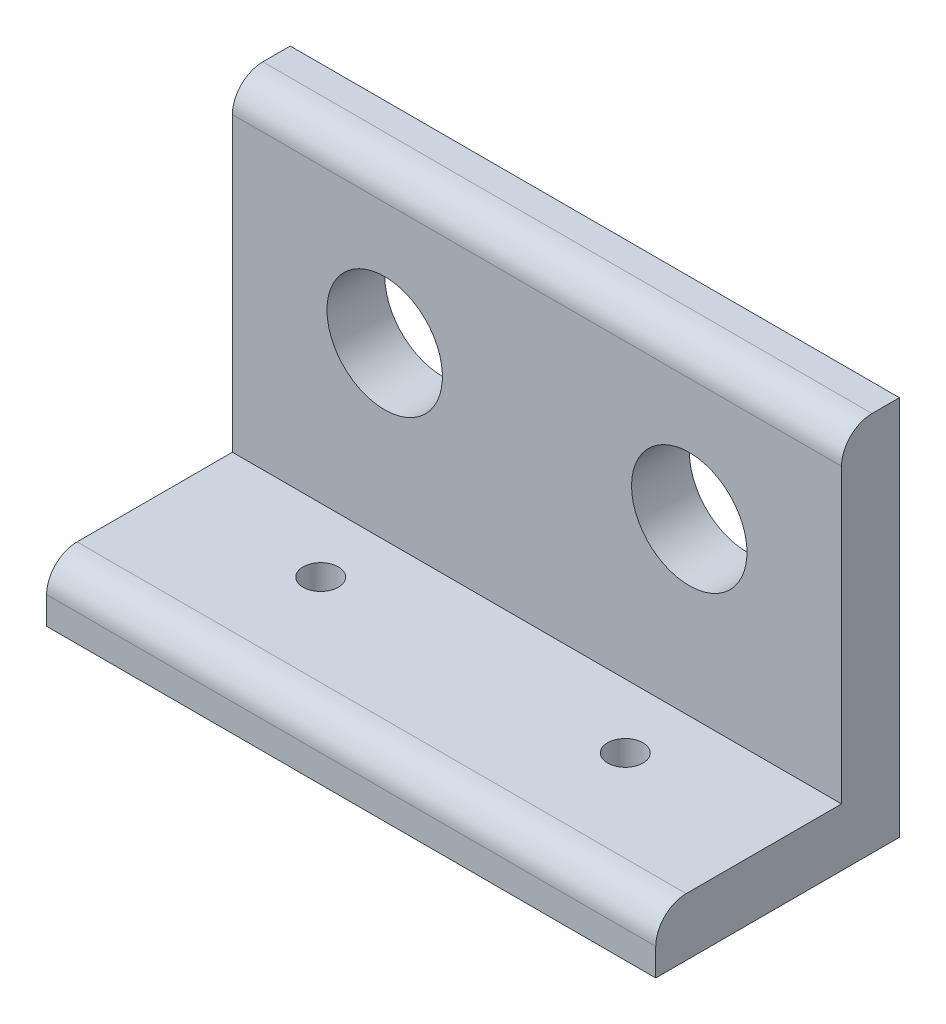
SolidWorks part; units mm, degrees
material "ABS"
ref_plane "Front Plane" through (0, 0, 0) normal (0, 0, 1) x (1, 0, 0)
ref_plane "Top Plane" through (0, 0, 0) normal (0, 1, 0) x (1, 0, 0)
ref_plane "Right Plane" through (0, 0, 0) normal (1, 0, 0) x (0, 0, -1)
sketch "Sketch1" plane through (0, 0, 0) normal (0, 1, 0) x (1, 0, 0)
  line L5 (0, 0) -> (50.8, 0)
  line L6 (0, 0) -> (0, 20.32)
  line L7 (0, 20.32) -> (50.8, 20.32)
  line L8 (50.8, 0) -> (50.8, 20.32)
  circle A0 centre (12.7, 10.16) radius 1.4732
  circle A1 centre (38.1, 10.16) radius 1.4732
  dimension "D3" = 2.9464
  dimension "D1" = 20.32
  dimension "D2" = 50.8
  dimension "D4" = 10.16
  dimension "D5" = 12.7
  dimension "D6" = 25.4
extrude "Boss-Extrude1" add sketch "Sketch1" along normal blind 4.826
sketch "Sketch2" plane through (0, 4.826, 0) normal (0, 1, 0) x (1, 0, 0)
  line L0 (50.8, 0) -> (50.8, 20.32) construction
  line L1 (0, 20.32) -> (50.8, 20.32)
  line L2 (0, 20.32) -> (0, 15.494)
  line L3 (0, 15.494) -> (50.8, 15.494)
  line L4 (50.8, 20.32) -> (50.8, 15.494)
  dimension "D1" = 4.826
extrude "Boss-Extrude2" add sketch "Sketch2" along normal blind 26.924
fillet "Fillet1" radius 2.54 2 edges at (25.4, 4.826, 0) (25.4, 31.75, -15.494)
sketch "Sketch3" plane through (0, 0, -20.32) normal (0, 0, -1) x (-1, 0, 0)
  line L0 (11.176, 0) -> (-11.176, 0) construction
  line L1 (-50.8, 31.75) -> (-50.8, 0) construction
  circle A0 centre (-38.1, 19.05) radius 4.8133
  circle A1 centre (-12.7, 19.05) radius 4.8133
  dimension "D1" = 9.6266
  dimension "D2" = 19.05
  dimension "D3" = 12.7
  dimension "D4" = 25.4
extrude "Cut-Extrude1" cut sketch "Sketch3" against normal blind 26.924
